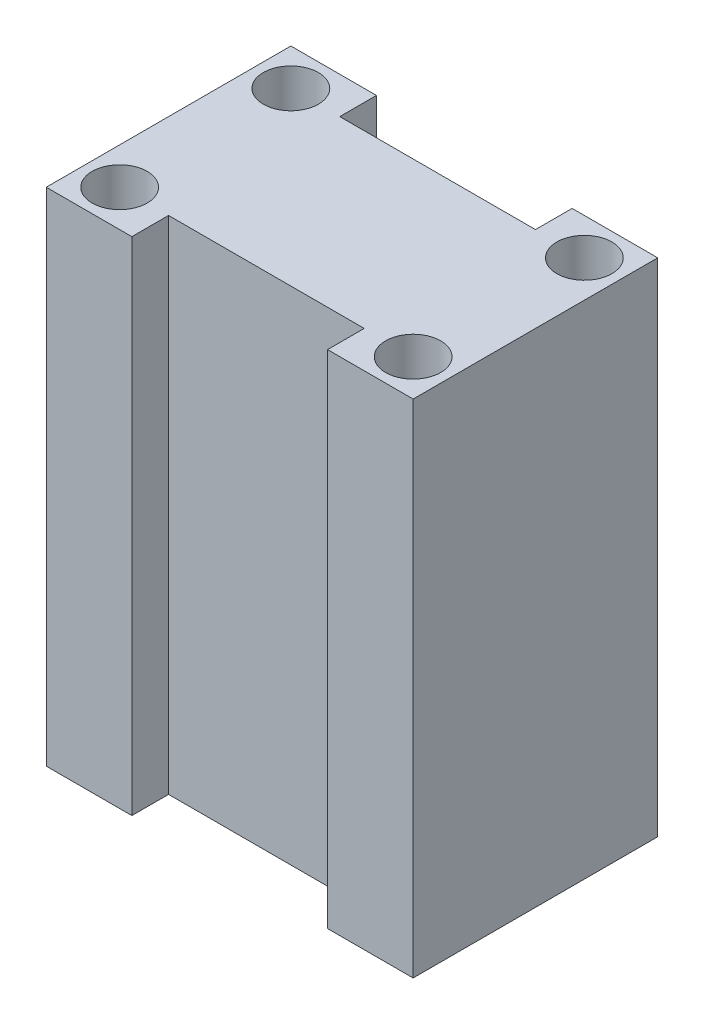
SolidWorks part; units mm, degrees
ref_plane "前视基准面" through (0, 0, 0) normal (0, 0, 1) x (1, 0, 0)
ref_plane "上视基准面" through (0, 0, 0) normal (0, 1, 0) x (1, 0, 0)
ref_plane "右视基准面" through (0, 0, 0) normal (1, 0, 0) x (0, 0, -1)
other "Configuration Table"
sketch "草图1" plane through (0, 0, 0) normal (0, 1, 0) x (1, 0, 0)
  line L1 (0, 0) -> (-30, 0)
  line L2 (0, 0) -> (0, 20)
  line L3 (0, 20) -> (-30, 20)
  line L4 (-30, 0) -> (-30, 20)
  dimension "D1" = 30
  dimension "D2" = 20
extrude "凸台-拉伸1" add sketch "草图1" along normal blind 41
sketch "草图17" plane through (0, 0, 0) normal (0, -1, 0) x (1, 0, 0)
  line L0 (-15, 0) -> (-15, -10) construction
  line L1 (-30, 0) -> (0, 0) construction
  line L2 (-23, -6) -> (-30, -6)
  line L7 (-23, -6) -> (-23, -14)
  line L8 (0, -14) -> (-7, -14)
  line L9 (-30, -20) -> (-30, 0) construction
  line L10 (-30, -14) -> (-23, -14)
  line L22 (-30, -6) -> (-30, -14)
  line L23 (0, -6) -> (0, -14)
  line L24 (-7, -6) -> (-7, -14)
  line L25 (-7, -6) -> (0, -6)
  line L26 (-15, -10) -> (-16.9272, -10) construction
  line L27 (-23, 0) -> (-7, 0)
  line L28 (-23, 0) -> (-23, -3)
  line L29 (-23, -3) -> (-7, -3)
  line L30 (-7, 0) -> (-7, -3)
  line L31 (-23, -17) -> (-7, -17)
  line L32 (-7, -20) -> (-7, -17)
  line L33 (-23, -20) -> (-7, -20)
  line L34 (-23, -20) -> (-23, -17)
  dimension "D1" = 3
  dimension "D2" = 16
  dimension "D3" = 7
extrude "切除-拉伸15" cut sketch "草图17" against normal up to next
sketch "草图20" plane through (0, 41, 0) normal (0, 1, 0) x (1, 0, 0)
  line L0 (-30, 0) -> (-27, 0) construction
  line L1 (-30, 0) -> (-23, 0) construction
  line L2 (-27, 0) -> (-27, 3) construction
  line L3 (-27, 3) -> (-27, 17) construction
  line L4 (-27, 17) -> (-3, 17) construction
  line L5 (-3, 17) -> (-3, 3) construction
  circle A0 centre (-27, 17) radius 2.25
  circle A1 centre (-27, 3) radius 2.25
  circle A2 centre (-3, 3) radius 2.25
  circle A3 centre (-3, 17) radius 2.25
  dimension "D6" = 4.5
  dimension "D1" = 3
  dimension "D2" = 3
  dimension "D3" = 14
  dimension "D4" = 24
  dimension "D5" = 14
extrude "切除-拉伸18" cut sketch "草图20" against normal blind 5
sketch "草图21" plane through (-7, 0, 0) normal (1, 0, 0) x (0, 0, -1)
  line L4 (6, 41) -> (6, 0)
  line L5 (6, 0) -> (14, 0)
  line L6 (14, 0) -> (14, 41)
  line L7 (14, 41) -> (6, 41)
  line L8 (6, 41) -> (6, 0)
  line L9 (6, 0) -> (14, 0)
  line L10 (14, 0) -> (14, 41)
  line L11 (14, 41) -> (6, 41)
  dimension "D1" = 0
extrude "凸台-拉伸2" add sketch "草图21" along normal up to surface (7 mm away) up to face at (0, 20.5, -17)
sketch "草图22" plane through (-23, 0, 0) normal (-1, 0, 0) x (0, 0, 1)
  line L4 (-14, 41) -> (-14, 0)
  line L5 (-14, 0) -> (-6, 0)
  line L6 (-6, 0) -> (-6, 41)
  line L7 (-6, 41) -> (-14, 41)
  line L8 (-14, 41) -> (-14, 0)
  line L9 (-14, 0) -> (-6, 0)
  line L10 (-6, 0) -> (-6, 41)
  line L11 (-6, 41) -> (-14, 41)
  dimension "D1" = 0
extrude "凸台-拉伸3" add sketch "草图22" along normal up to surface (7 mm away) up to face at (-30, 20.5, -17)
sketch "草图23" plane through (0, 0, 0) normal (0, -1, 0) x (1, 0, 0)
  circle A0 centre (-3, -17) radius 2.25 construction
  circle A1 centre (-27, -17) radius 2.25 construction
  circle A2 centre (-27, -3) radius 2.25 construction
  circle A3 centre (-3, -3) radius 2.25 construction
  circle A4 centre (-3, -17) radius 2.25
  circle A5 centre (-27, -17) radius 2.25
  circle A6 centre (-27, -3) radius 2.25
  circle A7 centre (-3, -3) radius 2.25
extrude "切除-拉伸19" cut sketch "草图23" against normal blind 5
